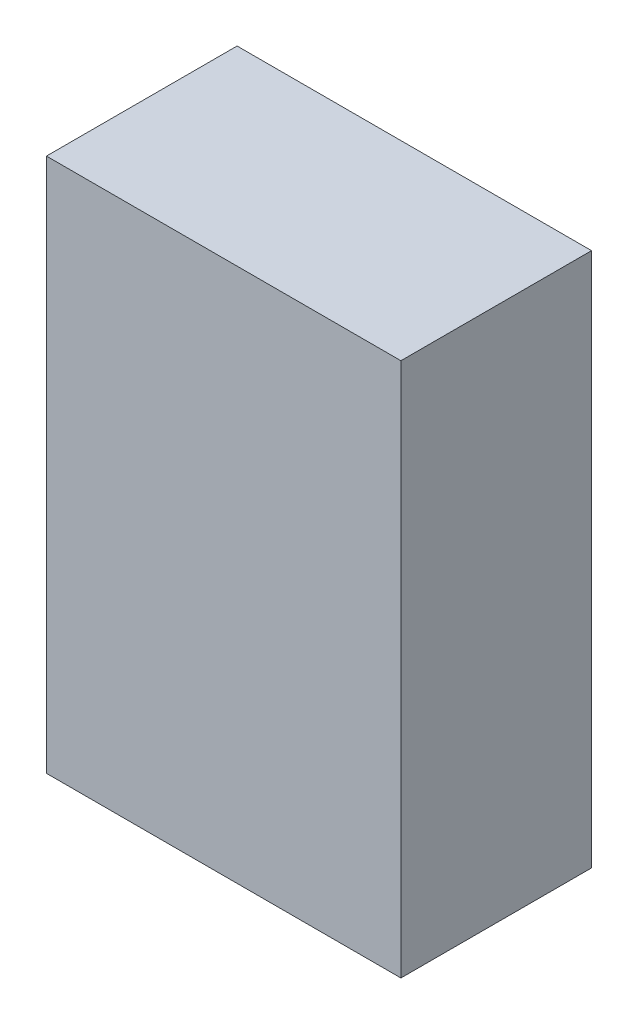
SolidWorks part; units mm, degrees
ref_plane "Front Plane" through (0, 0, 0) normal (0, 0, 1) x (1, 0, 0)
ref_plane "Top Plane" through (0, 0, 0) normal (0, 1, 0) x (1, 0, 0)
ref_plane "Right Plane" through (0, 0, 0) normal (1, 0, 0) x (0, 0, -1)
sketch "Sketch1" plane through (0, 0, 0) normal (0, 0, 1) x (1, 0, 0)
  line L0 (0, 2.8042) -> (1.8593, 2.8042)
  line L1 (1.8593, 2.8042) -> (1.8593, 0)
  line L2 (1.8593, 0) -> (0, 0)
  line L3 (0, 0) -> (0, 2.8042)
extrude "Component_Outline" add sketch "Sketch1" along normal blind 1 separate body
sketch3d "3DSketch1"
  line L0 (0, 0, 0) -> (1, 0, 0)
  line L1 (0, 0, 0) -> (0, 1, 0)
  line L2 (0, 0, 0) -> (0, 0, 1)
  point P0 (0, 0, 0)
